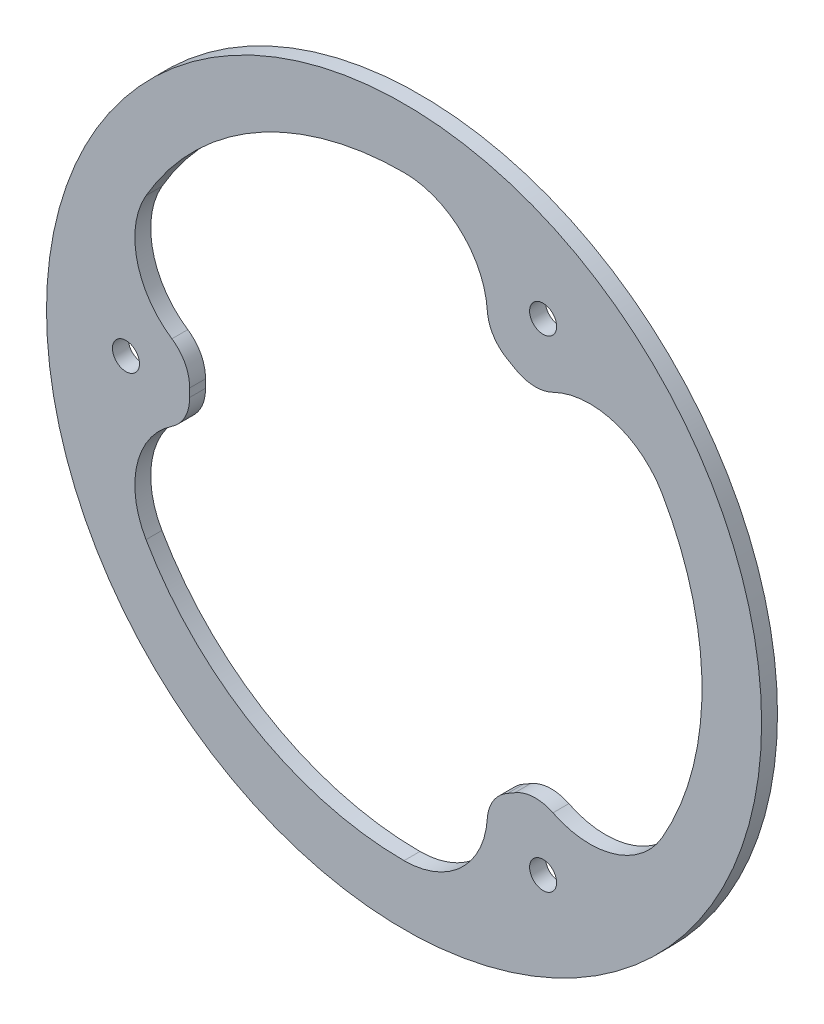
SolidWorks part; units mm, degrees
material "Сплав 2024"
ref_plane "Спереди" through (0, 0, 0) normal (0, 0, 1) x (1, 0, 0)
ref_plane "Сверху" through (0, 0, 0) normal (0, 1, 0) x (1, 0, 0)
ref_plane "Справа" through (0, 0, 0) normal (1, 0, 0) x (0, 0, -1)
sketch "Эскиз1" plane through (0, 0, 0) normal (0, 0, 1) x (1, 0, 0)
  circle A0 centre (0, 0) radius 40
  dimension "D1" = 80
extrude "Бобышка-Вытянуть1" add sketch "Эскиз1" along normal blind 12
sketch "Эскиз8" plane through (0, 0, 12) normal (0, 0, 1) x (1, 0, 0)
  circle A0 centre (0, 0) radius 45
  dimension "D1" = 90
extrude "Бобышка-Вытянуть3" add sketch "Эскиз8" along normal blind 2
sketch "Эскиз2" plane through (0, 0, 14) normal (0, 0, -1) x (-1, 0, 0)
  circle A0 centre (0, 0) radius 7.5
  dimension "D1" = 15
extrude "Вырез-Вытянуть1" cut sketch "Эскиз2" along normal through all
hole_wizard "Отверстие с зазором M31" positions "Эскиз4" profile "Эскиз3" hole size "M3" standard "Ansi Metric"
sketch "Эскиз4" plane through (-6.6635, -3.8899, 14) normal (0, 0, -1) x (-1, 0, 0)
  point P0 (20.5996, 37.0106)
sketch "Эскиз3" plane through (-27.2631, 33.1208, 14) normal (1, 0, 0) x (0, -1, 0)
  line L0 (0, 0) -> (0, 14)
  line L1 (0, 14) -> (1.7, 14)
  line L2 (1.7, 14) -> (1.7, 0)
  line L5 (1.7, 0) -> (0, 0)
  line L11 (0, -6.35) -> (0, 107.95) construction
  dimension "Диаметр сквозного отверстия" = 3.4
  dimension "Глубина сквозного отверстия" = 14
sketch "Эскиз10" plane through (0, 0, 0) normal (0, 0, -1) x (-1, 0, 0)
  line L1 (0, 49.276) -> (0, -49.5343) construction
  line L2 (46.4311, 26.807) -> (-46.4311, -26.807) construction
  arc A2 (32.476, -18.75) -> (14.2894, -8.25) centre (23.3827, -13.5) ccw
  arc A3 (32.476, 18.75) -> (0, 37.5) centre (0, 0) ccw
  circle A4 centre (0, 0) radius 27 construction
  arc A5 (0, 37.5) -> (0, 16.5) centre (0, 27) ccw
  arc A6 (14.2894, 8.25) -> (32.476, 18.75) centre (23.3827, 13.5) ccw
  arc A7 (14.2894, 8.25) -> (0, 16.5) centre (0, 0) ccw
  arc A8 (0, -16.5) -> (14.2894, -8.25) centre (0, 0) ccw
  arc A9 (0, -16.5) -> (0, -37.5) centre (0, -27) ccw
  arc A10 (0, -37.5) -> (32.476, -18.75) centre (0, 0) ccw
  arc A11 (-32.476, -18.75) -> (-14.2894, -8.25) centre (-23.3827, -13.5) ccw
  arc A12 (-14.2894, 8.25) -> (-14.2894, -8.25) centre (0, 0) ccw
  arc A13 (-14.2894, 8.25) -> (-32.476, 18.75) centre (-23.3827, 13.5) ccw
  arc A14 (-32.476, 18.75) -> (-32.476, -18.75) centre (0, 0) ccw
  point P28 (0, 0)
  dimension "D1" = 3
  dimension "D2" = 75
  dimension "D3" = 54
  dimension "D4" = 60
sketch "Эскиз11" plane through (0, 0, 14) normal (0, 0, 1) x (1, 0, 0)
  line L1 (6.25, 10.8253) -> (-6.25, -10.8253) construction
  line L2 (12.5, 0) -> (-12.5, 0) construction
  line L3 (-6.25, 10.8253) -> (6.25, -10.8253) construction
  circle A0 centre (0, 0) radius 12.5 construction
  dimension "D1" = 25
  dimension "D2" = 60
  dimension "D3" = 60
hole_wizard "Отверстие с зазором M32" positions "Эскиз13" profile "Эскиз12" hole size "M3" standard "Ansi Metric" end condition through all
sketch "Эскиз13" plane through (0, 0, 14) normal (0, 0, 1) x (1, 0, 0)
  point P0 (6.25, 10.8253)
  point P3 (-12.5, 0)
  point P9 (6.25, -10.8253)
sketch "Эскиз12" plane through (6.25, 10.8253, 14) normal (1, 0, 0) x (0, -1, 0)
  line L0 (0, 0) -> (0, 14)
  line L1 (0, 14) -> (1.7, 14)
  line L2 (1.7, 14) -> (1.7, 0)
  line L5 (1.7, 0) -> (0, 0)
  line L11 (0, -6.35) -> (0, 107.95) construction
  dimension "Диаметр сквозного отверстия" = 3.4
  dimension "Глубина сквозного отверстия" = 14
extrude "Вырез-Вытянуть2" cut sketch "Эскиз10" against normal through all
sketch "Эскиз14" plane through (0, 0, 0) normal (0, 0, -1) x (-1, 0, 0)
  line L2 (-55.8661, 0) -> (55.9948, 0) construction
  line L3 (-20, 34.641) -> (20, -34.641) construction
  line L4 (20, 34.641) -> (-20, -34.641) construction
  circle A0 centre (0, 0) radius 40 construction
  circle A1 centre (0, 0) radius 40 construction
  circle A2 centre (0, 0) radius 35 construction
  dimension "D3" = 70
  dimension "D1" = 60
  dimension "D2" = 60
hole_wizard "Отверстие с зазором M33" positions "Эскиз16" profile "Эскиз15" hole size "M3" standard "Ansi Metric" end condition through all
sketch "Эскиз16" plane through (0, 0, 0) normal (0, 0, -1) x (-1, 0, 0)
  line L0 (-20, 34.641) -> (20, -34.641) construction
  line L1 (20, 34.641) -> (-20, -34.641) construction
  line L2 (-55.8661, 0) -> (55.9948, 0) construction
  circle A0 centre (0, 0) radius 35 construction
  point P0 (-17.5, 30.3109)
  point P6 (35, 0)
  point P12 (-17.5, -30.3109)
sketch "Эскиз15" plane through (17.5, 30.3109, 0) normal (1, 0, 0) x (0, 1, 0)
  line L0 (0, 0) -> (0, 14)
  line L1 (0, 14) -> (1.7, 14)
  line L2 (1.7, 14) -> (1.7, 0)
  line L5 (1.7, 0) -> (0, 0)
  line L11 (0, -6.35) -> (0, 107.95) construction
  dimension "Диаметр сквозного отверстия" = 3.4
  dimension "Глубина сквозного отверстия" = 14
sketch "Эскиз17" plane through (0, 0, 0) normal (0, 0, -1) x (-1, 0, 0)
  circle A0 centre (0, 0) radius 42.2429
extrude "Вырез-Вытянуть3" cut sketch "Эскиз17" against normal up to surface (12 mm away) up to face at (45, 0, 12)
sketch "Эскиз18" plane through (0, 0, 12) normal (0, 0, -1) x (-1, 0, 0)
  circle A0 centre (0, 0) radius 27
  dimension "D1" = 54
extrude "Вырез-Вытянуть4" cut sketch "Эскиз18" against normal through all
fillet "Скругление1" radius 5 6 edges at (-26.7643, 3.5595, 13) (-26.7643, -3.5595, 13) (16.4648, -21.3989, 13) (10.2996, -24.9583, 13) (10.2996, 24.9583, 13) (16.4648, 21.3989, 13)
sketch "Эскиз19" plane through (0, 0, 0) normal (0, 0, 1) x (1, 0, 0)
  line L0 (45, -24.7185) -> (45, -45) construction
  line L1 (45, -45) -> (29.4621, -45) construction
  circle A0 centre (0, 0) radius 45 construction
